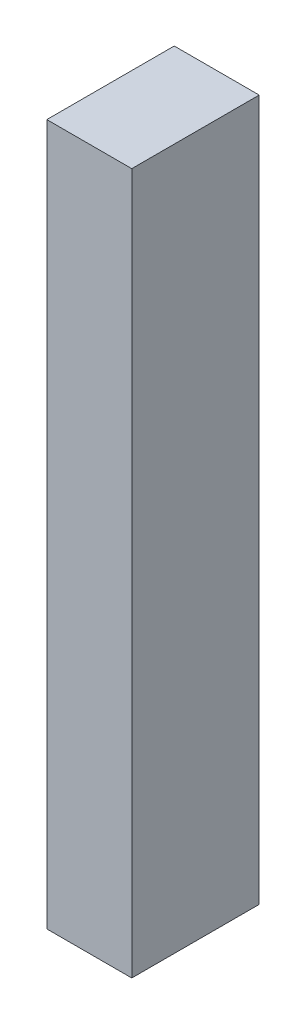
SolidWorks part; units mm, degrees
material "Balsa"
ref_plane "Front Plane" through (0, 0, 0) normal (0, 0, 1) x (1, 0, 0)
ref_plane "Top Plane" through (0, 0, 0) normal (0, 1, 0) x (1, 0, 0)
ref_plane "Right Plane" through (0, 0, 0) normal (1, 0, 0) x (0, 0, -1)
sketch "Sketch1" plane through (0, 0, 0) normal (0, 1, 0) x (1, 0, 0)
  line L1 (-25.4, 38.1) -> (25.4, 38.1)
  line L2 (-25.4, 38.1) -> (-25.4, -38.1)
  line L3 (-25.4, -38.1) -> (25.4, -38.1)
  line L4 (25.4, 38.1) -> (25.4, -38.1)
  line L5 (0, -38.1) -> (0, 38.1) construction
  line L6 (-25.4, 0) -> (25.4, 0) construction
  point P0 (0, 0)
  dimension "D1" = 50.8
  dimension "D2" = 76.2
extrude "Boss-Extrude1" add sketch "Sketch1" along normal blind 419.1
